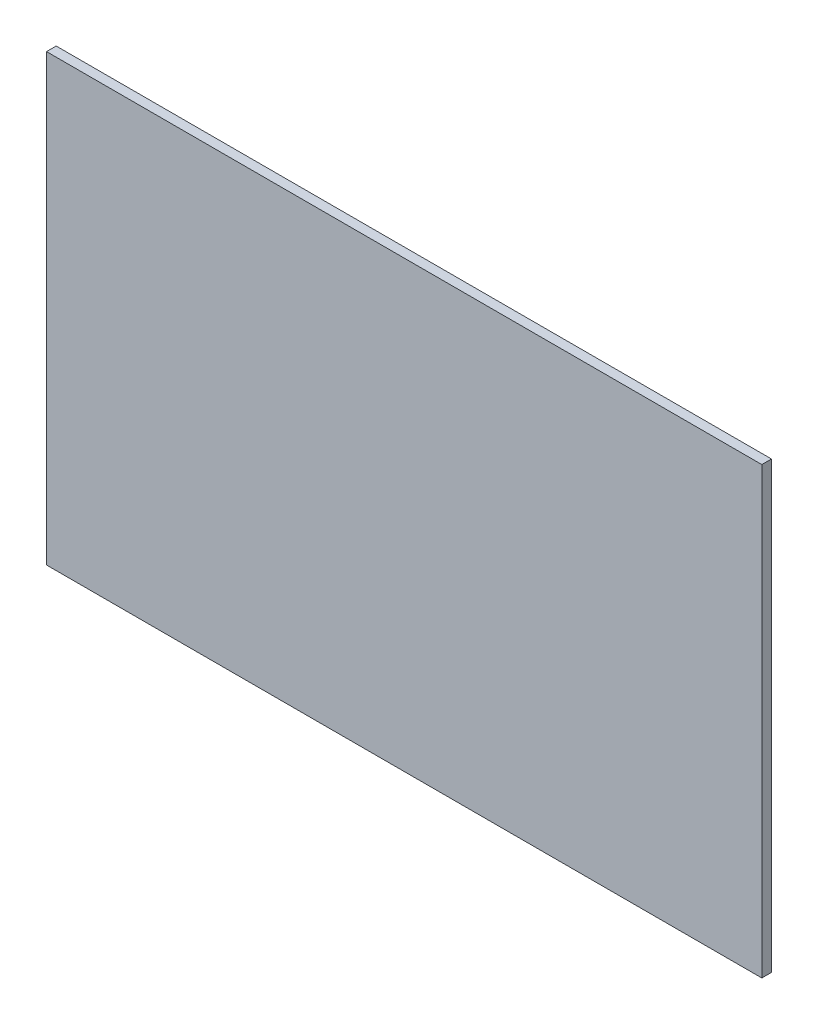
SolidWorks part; units mm, degrees
ref_plane "Front Plane" through (0, 0, 0) normal (0, 0, 1) x (1, 0, 0)
ref_plane "Top Plane" through (0, 0, 0) normal (0, 1, 0) x (1, 0, 0)
ref_plane "Right Plane" through (0, 0, 0) normal (1, 0, 0) x (0, 0, -1)
sketch "Sketch1" plane through (0, 0, 0) normal (0, 0, 1) x (1, 0, 0)
  line L1 (0, 0) -> (469.9, 0)
  line L2 (0, 0) -> (0, 292.1)
  line L3 (0, 292.1) -> (469.9, 292.1)
  line L4 (469.9, 0) -> (469.9, 292.1)
  dimension "D1" = 469.9
  dimension "D2" = 292.1
extrude "Boss-Extrude1" add sketch "Sketch1" along normal blind 6.35
